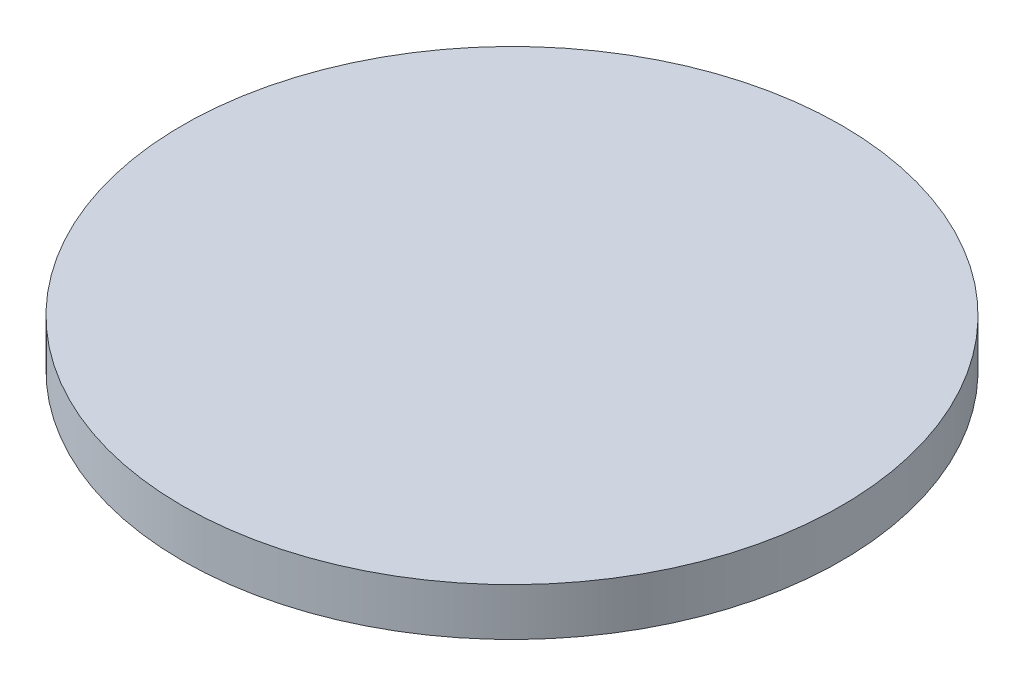
SolidWorks part; units mm, degrees
material "Nickel"
ref_plane "Front Plane" through (0, 0, 0) normal (0, 0, 1) x (1, 0, 0)
ref_plane "Top Plane" through (0, 0, 0) normal (0, 1, 0) x (1, 0, 0)
ref_plane "Right Plane" through (0, 0, 0) normal (1, 0, 0) x (0, 0, -1)
sketch "Sketch1" plane through (0, 0, 0) normal (0, 1, 0) x (1, 0, 0)
  circle A0 centre (0, 0) radius 12.1285
  dimension "D1" = 24.257
extrude "Boss-Extrude1" add sketch "Sketch1" along normal blind 1.75
